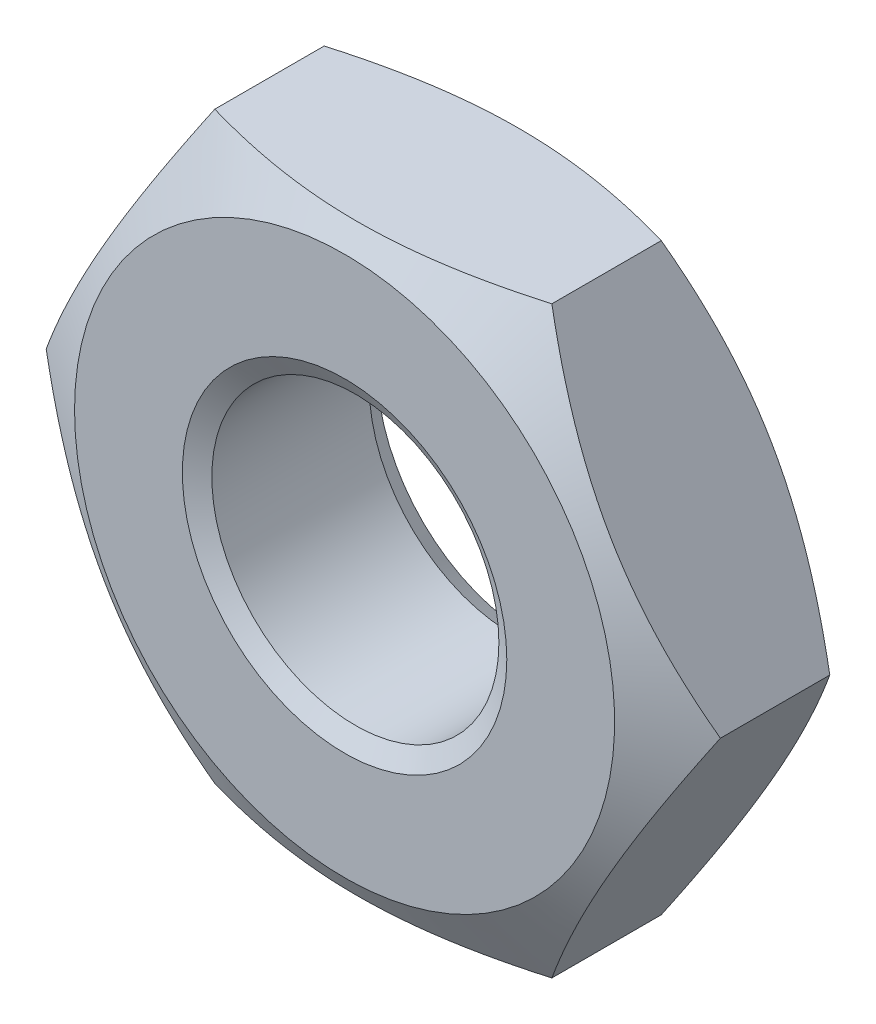
SolidWorks part; units mm, degrees
ref_plane "Front" through (0, 0, 0) normal (0, 0, 1) x (1, 0, 0)
ref_plane "Top" through (0, 0, 0) normal (0, 1, 0) x (1, 0, 0)
ref_plane "Right" through (0, 0, 0) normal (1, 0, 0) x (0, 0, -1)
sketch "Sketch1" plane through (0, 0, 0) normal (0, 0, 1) x (1, 0, 0)
  line L1 (2.8868, -5) -> (5.7735, 0)
  line L2 (5.7735, 0) -> (2.8868, 5)
  line L3 (2.8868, 5) -> (-2.8868, 5)
  line L4 (-2.8868, 5) -> (-5.7735, 0)
  line L5 (-5.7735, 0) -> (-2.8868, -5)
  line L6 (-2.8868, -5) -> (2.8868, -5)
  circle A0 centre (0, 0) radius 5 construction
  circle A1 centre (0, 0) radius 2.4585
  dimension "D" = 4.917
  dimension "s" = 10
extrude "BaseNut" add sketch "Sketch1" against normal blind 3.2
cosmetic thread "ThreadCosmetic1" [suppressed] parameters "D"=6
sketch "Sketch2" plane through (0, 0, 0) normal (0, 1, 0) x (1, 0, 0)
  line L0 (-5.7735, 3.2) -> (-4.625, 3.2)
  line L2 (-4.625, 3.2) -> (-5.7735, 2.5369)
  line L3 (-5.7735, 2.5369) -> (-5.7735, 3.2)
  line L4 (0, 3.3759) -> (0, -9.8171) construction
  line L6 (-9.7712, 1.6) -> (9.8853, 1.6) construction
  line L7 (-5.7735, 0.6631) -> (-5.7735, 0)
  line L8 (-4.625, 0) -> (-5.7735, 0.6631)
  line L9 (-5.7735, 0) -> (-4.625, 0)
  dimension "dw" = 9.25
  dimension "D1" = 30
  dimension "D2" = 1.6
revolve "Double-Chamfer" cut sketch "Sketch2" angle 360 about L4
chamfer "EndChamfer" distance 0.32 angle 30 2 edges at (2.4585, 0, -3.2) (2.4585, 0, 0)
sketch "Sketch3" plane through (0, 0, 0) normal (0, 1, 0) x (1, 0, 0)
  line L0 (0, 6.7075) -> (0, -2.1252) construction
  line L1 (1.917, 3.1507) -> (2.4585, 3.1507)
  line L2 (2.4585, 3.1507) -> (2.9275, 2.88)
  line L3 (2.9275, 2.88) -> (2.4585, 2.6092)
  line L4 (2.4585, 2.6092) -> (1.917, 2.6092)
  line L5 (1.917, 2.6092) -> (1.917, 3.1507)
  line L6 (2.4585, 2.88) -> (-2.4585, 2.88) construction
  dimension "D1" = 0.5415
  dimension "D2" = 4.917
revolve "Cut-Revolve10" [suppressed] cut sketch "Sketch3" angle 360 about L0
pattern_linear "LPattern10" [suppressed] count 4 spacing 0.6498 along (0, 0, 1)
equation "\"dw@Sketch2\" = \"s@Sketch1\"-0.75"
equation "\"D2@Sketch2\" = \"m@BaseNut\" / 2"
equation "\"D1@EndChamfer\" = \"m@BaseNut\" / 10"
equation "\"D2@Sketch3\" = \"D@Sketch1\""
equation "\"D1@Sketch3\" = (  \"D@ThreadCosmetic1\" - \"D@Sketch1\" )  / 2"
equation "\"D3@LPattern10\" = \"D1@Sketch3\" * 1.2"
equation "\"D1@LPattern10\" = (  \"m@BaseNut\" - \"D1@EndChamfer\" )  / \"D3@LPattern10\" "
